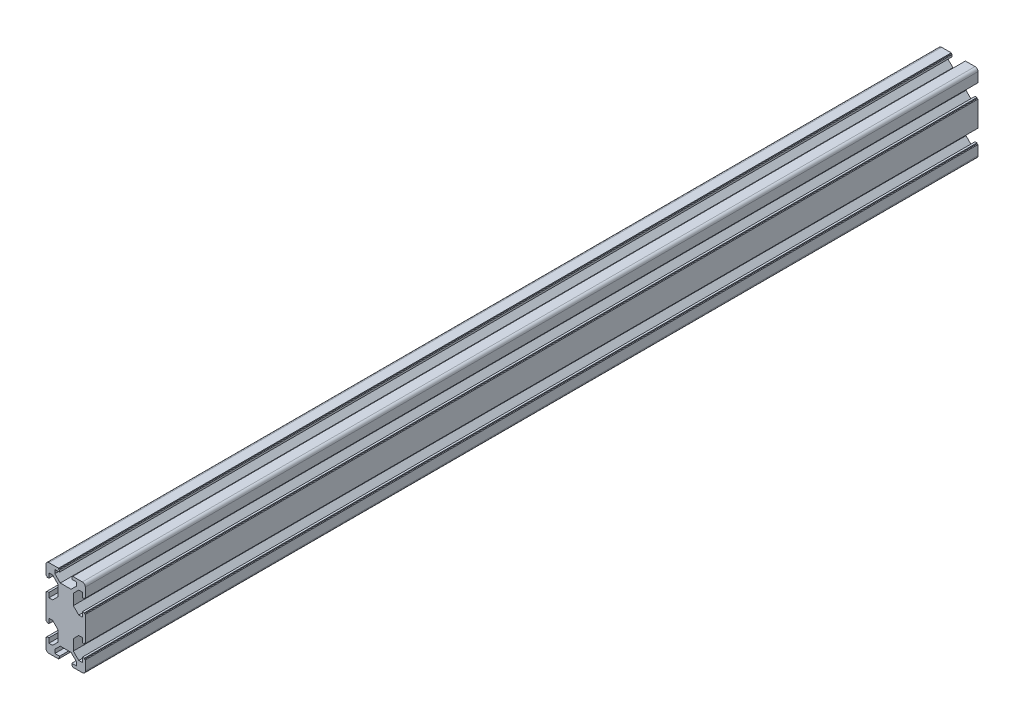
SolidWorks part; units mm, degrees
ref_plane "Plane1" through (0, 0, 0) normal (0, 0, 1) x (1, 0, 0)
ref_plane "Plane2" through (0, 0, 0) normal (0, 1, 0) x (1, 0, 0)
ref_plane "Plane3" through (0, 0, 0) normal (1, 0, 0) x (0, 0, -1)
sketch "Sketch1" plane through (0, 0, 0) normal (0, 0, 1) x (1, 0, 0)
  line L0 (-3.6, 10) -> (-3.6, 9.5)
  line L1 (-3.6, 9.5) -> (-3.1, 9.5)
  line L2 (-3.1, 9.5) -> (-3.1, 8.5)
  line L3 (-3.1, 8.5) -> (-5.5, 8.5)
  line L4 (8.85, -10) -> (2.75, -3.9)
  line L5 (-10, -16.4) -> (-10, -3.6)
  line L6 (8.5, 10) -> (3.6, 10)
  line L7 (10, 8.5) -> (10, 3.6)
  line L8 (0, 14.8756) -> (0, 0) construction
  line L9 (0, 0) -> (10, 0) construction
  line L10 (-5.5, 8.5) -> (-5.5, 6.65)
  line L11 (-5.5, 6.65) -> (-2.75, 3.9)
  line L12 (-2.75, 3.9) -> (2.75, 3.9)
  line L13 (5.5, 6.65) -> (2.75, 3.9)
  line L14 (5.5, 8.5) -> (5.5, 6.65)
  line L15 (3.1, 8.5) -> (5.5, 8.5)
  line L16 (3.1, 9.5) -> (3.1, 8.5)
  line L17 (3.6, 9.5) -> (3.1, 9.5)
  line L18 (3.6, 10) -> (3.6, 9.5)
  line L19 (-3.6, 10) -> (-8.5, 10)
  line L20 (10, 3.6) -> (9.5, 3.6)
  line L21 (9.5, 3.6) -> (9.5, 3.1)
  line L22 (9.5, 3.1) -> (8.5, 3.1)
  line L23 (8.5, 3.1) -> (8.5, 5.5)
  line L24 (8.5, 5.5) -> (6.65, 5.5)
  line L25 (6.65, 5.5) -> (3.9, 2.75)
  line L26 (3.9, 2.75) -> (3.9, -2.75)
  line L27 (6.65, -5.5) -> (3.9, -2.75)
  line L28 (8.5, -5.5) -> (6.65, -5.5)
  line L29 (8.5, -3.1) -> (8.5, -5.5)
  line L30 (9.5, -3.1) -> (8.5, -3.1)
  line L31 (9.5, -3.6) -> (9.5, -3.1)
  line L32 (10, -3.6) -> (9.5, -3.6)
  line L33 (8.85, -10) -> (2.75, -16.1)
  line L34 (-8.85, -10) -> (-2.75, -16.1)
  line L35 (-8.85, -10) -> (-2.75, -3.9)
  line L39 (2.75, -3.9) -> (-2.75, -3.9)
  line L46 (-10, -3.6) -> (-9.5, -3.6)
  line L47 (-9.5, -3.6) -> (-9.5, -3.1)
  line L48 (-9.5, -3.1) -> (-8.5, -3.1)
  line L49 (-8.5, -3.1) -> (-8.5, -5.5)
  line L50 (-8.5, -5.5) -> (-6.65, -5.5)
  line L51 (-6.65, -5.5) -> (-3.9, -2.75)
  line L52 (-3.9, -2.75) -> (-3.9, 2.75)
  line L53 (-6.65, 5.5) -> (-3.9, 2.75)
  line L54 (-8.5, 5.5) -> (-6.65, 5.5)
  line L55 (-8.5, 3.1) -> (-8.5, 5.5)
  line L56 (-9.5, 3.1) -> (-8.5, 3.1)
  line L57 (-9.5, 3.6) -> (-9.5, 3.1)
  line L58 (-10, 3.6) -> (-9.5, 3.6)
  line L60 (-10, 3.6) -> (-10, 8.5)
  line L61 (10, -3.6) -> (10, -16.4)
  line L66 (-8.5, -30) -> (-3.6, -30)
  line L67 (-10, -28.5) -> (-10, -23.6)
  line L72 (-2.75, -16.1) -> (2.75, -16.1)
  line L80 (10, -16.4) -> (9.5, -16.4)
  line L81 (9.5, -16.4) -> (9.5, -16.9)
  line L82 (9.5, -16.9) -> (8.5, -16.9)
  line L83 (8.5, -16.9) -> (8.5, -14.5)
  line L84 (8.5, -14.5) -> (6.65, -14.5)
  line L85 (6.65, -14.5) -> (3.9, -17.25)
  line L86 (3.9, -17.25) -> (3.9, -22.75)
  line L87 (6.65, -25.5) -> (3.9, -22.75)
  line L88 (8.5, -25.5) -> (6.65, -25.5)
  line L89 (8.5, -23.1) -> (8.5, -25.5)
  line L90 (9.5, -23.1) -> (8.5, -23.1)
  line L91 (9.5, -23.6) -> (9.5, -23.1)
  line L92 (10, -23.6) -> (9.5, -23.6)
  line L93 (3.6, -30) -> (3.6, -29.5)
  line L94 (3.6, -29.5) -> (3.1, -29.5)
  line L95 (3.1, -29.5) -> (3.1, -28.5)
  line L96 (3.1, -28.5) -> (5.5, -28.5)
  line L97 (5.5, -28.5) -> (5.5, -26.65)
  line L98 (5.5, -26.65) -> (2.75, -23.9)
  line L99 (2.75, -23.9) -> (-2.75, -23.9)
  line L100 (-5.5, -26.65) -> (-2.75, -23.9)
  line L101 (-5.5, -28.5) -> (-5.5, -26.65)
  line L102 (-3.1, -28.5) -> (-5.5, -28.5)
  line L103 (-3.1, -29.5) -> (-3.1, -28.5)
  line L104 (-3.6, -29.5) -> (-3.1, -29.5)
  line L105 (-3.6, -30) -> (-3.6, -29.5)
  line L106 (-10, -23.6) -> (-9.5, -23.6)
  line L107 (-9.5, -23.6) -> (-9.5, -23.1)
  line L108 (-9.5, -23.1) -> (-8.5, -23.1)
  line L109 (-8.5, -23.1) -> (-8.5, -25.5)
  line L110 (-8.5, -25.5) -> (-6.65, -25.5)
  line L111 (-6.65, -25.5) -> (-3.9, -22.75)
  line L112 (-3.9, -22.75) -> (-3.9, -17.25)
  line L113 (-6.65, -14.5) -> (-3.9, -17.25)
  line L114 (-8.5, -14.5) -> (-6.65, -14.5)
  line L115 (-8.5, -16.9) -> (-8.5, -14.5)
  line L116 (-9.5, -16.9) -> (-8.5, -16.9)
  line L117 (-9.5, -16.4) -> (-9.5, -16.9)
  line L118 (-10, -16.4) -> (-9.5, -16.4)
  line L119 (3.6, -30) -> (8.5, -30)
  line L121 (10, -23.6) -> (10, -28.5)
  line L122 (0, -20) -> (10, -20) construction
  line L123 (-20.8285, -10) -> (-3.6, -10) [skipped]
  line L124 (3.6, -10) -> (3.6, -9.5) [skipped]
  line L125 (3.6, -10) -> (3.6, -9.5) [skipped]
  line L126 (3.6, -9.5) -> (3.1, -9.5) [skipped]
  line L127 (3.6, -9.5) -> (3.1, -9.5) [skipped]
  line L128 (3.1, -9.5) -> (3.1, -8.5) [skipped]
  line L129 (3.1, -9.5) -> (3.1, -8.5) [skipped]
  line L130 (3.1, -8.5) -> (5.5, -8.5) [skipped]
  line L131 (3.1, -8.5) -> (5.5, -8.5) [skipped]
  line L132 (-3.1, -8.5) -> (-5.5, -8.5) [skipped]
  line L133 (-3.1, -8.5) -> (-5.5, -8.5) [skipped]
  line L134 (-3.1, -9.5) -> (-3.1, -8.5) [skipped]
  line L135 (-3.1, -9.5) -> (-3.1, -8.5) [skipped]
  line L136 (-3.6, -9.5) -> (-3.1, -9.5) [skipped]
  line L137 (-3.6, -9.5) -> (-3.1, -9.5) [skipped]
  line L138 (-3.6, -10) -> (-3.6, -9.5) [skipped]
  line L139 (-3.6, -10) -> (-3.6, -9.5) [skipped]
  line L140 (3.6, -10) -> (14.9874, -10) [skipped]
  line L141 (-3.6, -10) -> (-3.6, -10.5) [skipped]
  line L142 (-3.6, -10.5) -> (-3.1, -10.5) [skipped]
  line L143 (-3.1, -10.5) -> (-3.1, -11.5) [skipped]
  line L144 (-3.1, -11.5) -> (-5.5, -11.5) [skipped]
  line L145 (8.5, -10) -> (3.6, -10) [skipped]
  line L146 (3.1, -11.5) -> (5.5, -11.5) [skipped]
  line L147 (3.1, -10.5) -> (3.1, -11.5) [skipped]
  line L148 (3.6, -10.5) -> (3.1, -10.5) [skipped]
  line L149 (3.6, -10) -> (3.6, -10.5) [skipped]
  line L150 (-3.6, -10) -> (-8.5, -10) [skipped]
  line L151 (-10, -16.4) -> (-10, -11.5) [skipped]
  line L152 (10, -11.5) -> (10, -16.4) [skipped]
  line L153 (-5.5, -8.5) -> (-5.5, -6.65) [skipped]
  line L154 (-5.5, -8.5) -> (-5.5, -6.65) [skipped]
  line L155 (5.5, -8.5) -> (5.5, -6.65) [skipped]
  line L156 (5.5, -8.5) -> (5.5, -6.65) [skipped]
  line L157 (5.5, -11.5) -> (5.5, -13.35) [skipped]
  line L158 (-5.5, -11.5) -> (-5.5, -13.35) [skipped]
  line L159 (-12.2446, -13.3946) -> (-10, -11.15) [skipped]
  line L160 (-12.2446, -13.3946) -> (-10, -11.15) [skipped]
  line L161 (13.644, -5.206) -> (10, -8.85) [skipped]
  line L162 (12.1963, -13.3463) -> (10, -11.15) [skipped]
  line L163 (12.1963, -13.3463) -> (10, -11.15) [skipped]
  line L164 (-11.1344, -7.7156) -> (-10, -8.85) [skipped]
  circle A0 centre (0, 0) radius 2.5
  arc A1 (-10, 8.5) -> (-8.5, 10) centre (-8.5, 8.5) cw
  arc A2 (10, 8.5) -> (8.5, 10) centre (8.5, 8.5) ccw
  arc A3 (10, -28.5) -> (8.5, -30) centre (8.5, -28.5) cw
  arc A4 (-10, -28.5) -> (-8.5, -30) centre (-8.5, -28.5) ccw
  circle A5 centre (0, -20) radius 2.5
  arc A10 (-8.5, -10) -> (-10, -16.2676) centre (-13.642, -12.0827) cw [skipped]
  arc A11 (8.5, -10) -> (10, -11.9856) centre (9.9185, -10.4878) ccw [skipped]
  arc A12 (-10, -11.5) -> (-8.5, -10) centre (-8.5, -11.5) cw [skipped]
  arc A13 (10, -11.5) -> (8.5, -10) centre (8.5, -11.5) ccw [skipped]
  arc A14 (8.5, -30) -> (10, -31.9856) centre (9.9185, -30.4878) ccw [skipped]
  arc A15 (-8.5, -30) -> (-10, -36.2676) centre (-13.642, -32.0827) cw [skipped]
  point P0 (-10, 0)
  point P1 (10, 0)
  point P2 (0, 10)
  point P4 (0, 0)
  point P5 (0, -10)
  point P6 (-10, -10)
  point P7 (10, 10)
  point P8 (-10, 10)
  point P12 (-10, -10)
  point P13 (10, -10)
  point P15 (0, -10)
  point P16 (10, -10)
  point P36 (-10, 10)
  point P39 (10, 10)
  point P43 (-10, -20)
  point P44 (10, -20)
  point P88 (0, -30)
  point P89 (0, -20)
  point P90 (-10, -30)
  point P91 (10, -30)
extrude "凸台-拉伸1" add sketch "Sketch1" along normal blind 454 contours L19 A1 L60 L58 L57 L56 L55 L54 L53 L52 L51 L50 L49 L48 L47 L46 L5 L118 L117 L116 L115 L114 L113 L112 L111 L110 L109 L108 L107 L106 L67 A4 L66 L105 L104 L103 L102 L101 L100 L99 L98 L97 L96 L95 L94 L93 L119 A3 L121 L92 L91 L90 L89 L88 L87 L86 L85 L84 L83 L82 L81 L80 L61 L32 L31 L30 L29 L28 L27 L26 L25 L24 L23 L22 L21 L20 L7 A2 L6 L18 L17 L16 L15 L14 L13 L12 L11 L10 L3 L2 L1 L0
